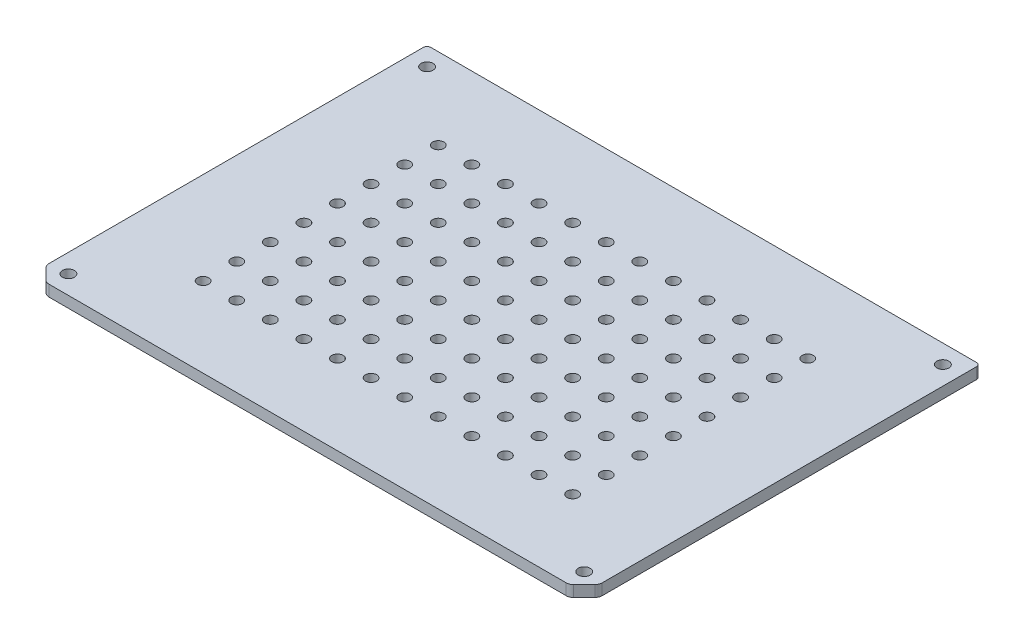
SolidWorks part; units mm, degrees
ref_plane "Front Plane" through (0, 0, 0) normal (0, 0, 1) x (1, 0, 0)
ref_plane "Top Plane" through (0, 0, 0) normal (0, 1, 0) x (1, 0, 0)
ref_plane "Right Plane" through (0, 0, 0) normal (1, 0, 0) x (0, 0, -1)
sketch "Sketch1" plane through (0, 0, 0) normal (0, 1, 0) x (1, 0, 0)
  line L0 (-74.1, 53.05) -> (74.1, 53.05)
  line L1 (-64.1, 43.05) -> (64.1, 43.05) construction
  line L2 (-64.1, 43.05) -> (-64.1, -43.05) construction
  line L3 (-64.1, -43.05) -> (64.1, -43.05) construction
  line L4 (64.1, 43.05) -> (64.1, -43.05) construction
  line L5 (-64.1, 43.05) -> (64.1, -43.05) construction
  line L6 (-64.1, -43.05) -> (64.1, 43.05) construction
  line L7 (74.1, 53.05) -> (74.1, -53.05)
  line L8 (-74.1, -53.05) -> (74.1, -53.05)
  line L9 (-74.1, 53.05) -> (-74.1, -53.05)
  line L10 (-74.1, 53.05) -> (-64.1, 43.05) construction
  line L11 (-74.1, 0) -> (74.1, 0) construction
  line L12 (0, 53.05) -> (0, -53.05) construction
  circle A0 centre (-69.1, 48.05) radius 1.6
  circle A1 centre (-69.1, -48.05) radius 1.6
  circle A2 centre (69.1, -48.05) radius 1.6
  circle A3 centre (69.1, 48.05) radius 1.6
  point P0 (0, 0)
  dimension "D4" = 3.2
  dimension "D1" = 128.2
  dimension "D2" = 86.1
  dimension "D3" = 10
extrude "Boss-Extrude1" add sketch "Sketch1" along normal blind 3
sketch "Sketch2" plane through (0, 3, 0) normal (0, 1, 0) x (-1, 0, 0)
  line L1 (63.8, -42.75) -> (-63.8, -42.75) construction
  line L2 (63.8, -42.75) -> (63.8, 42.75) construction
  line L3 (63.8, 42.75) -> (-63.8, 42.75) construction
  line L4 (-63.8, -42.75) -> (-63.8, 42.75) construction
  line L5 (63.8, -42.75) -> (-63.8, 42.75) construction
  line L6 (63.8, 42.75) -> (-63.8, -42.75) construction
  circle A0 centre (49.4, -31.35) radius 1.5
  point P0 (0, 0)
  dimension "D3" = 14.4
  dimension "D4" = 11.4
  dimension "D5" = 3
  dimension "D1" = 127.6
  dimension "D2" = 85.5
extrude "Cut-Extrude1" cut sketch "Sketch2" against normal blind 3
pattern_linear "LPattern1" count 8 spacing 9 along (0, 0, 1) count 12 spacing 9 along (1, 0, 0) of "Cut-Extrude1"
fillet "Fillet1" radius 1 4 edges at (74.1, 1.5, -53.05) (74.1, 1.5, 53.05) (-74.1, 1.5, 53.05) (-74.1, 1.5, -53.05)
sketch "Sketch3" plane through (0, 3, 0) normal (0, 1, 0) x (-1, 0, 0)
  line L0 (77.1, 46.05) -> (67.1, 56.05)
  line L1 (67.1, 56.05) -> (77.1, 56.05)
  line L2 (77.1, 56.05) -> (77.1, 46.05)
  line L3 (0, -53.05) -> (0, 53.05) construction
  line L4 (-73.1, -53.05) -> (73.1, -53.05) construction
  line L5 (73.1, 53.05) -> (-73.1, 53.05) construction
  line L6 (-77.1, 56.05) -> (-77.1, 46.05)
  line L7 (-67.1, 56.05) -> (-77.1, 56.05)
  line L8 (-77.1, 46.05) -> (-67.1, 56.05)
  line L10 (74.1, -52.05) -> (74.1, 52.05) construction
  dimension "D1" = 45
  dimension "D2" = 10
  dimension "D3" = 3
  dimension "D4" = 3
extrude "Cut-Extrude2" cut sketch "Sketch3" against normal blind 3
fillet "Fillet2" radius 2 4 edges at (74.1, 1.5, 49.05) (70.1, 1.5, 53.05) (-70.1, 1.5, 53.05) (-74.1, 1.5, 49.05)
